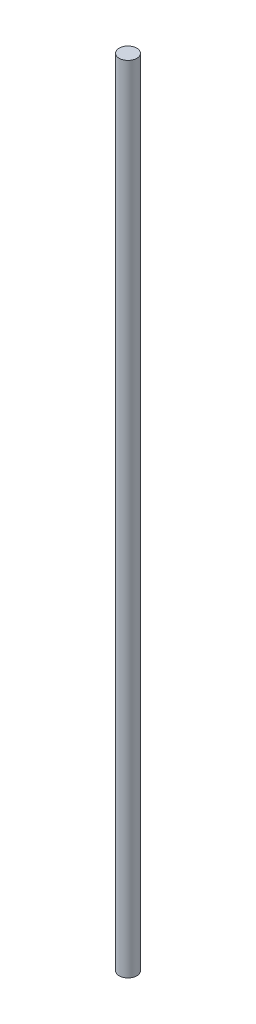
SolidWorks part; units mm, degrees
ref_plane "Спереди" through (0, 0, 0) normal (0, 0, 1) x (1, 0, 0)
ref_plane "Сверху" through (0, 0, 0) normal (0, 1, 0) x (1, 0, 0)
ref_plane "Справа" through (0, 0, 0) normal (1, 0, 0) x (0, 0, -1)
sketch "Эскиз1" plane through (0, 0, 0) normal (0, 1, 0) x (1, 0, 0)
  circle A0 centre (0, 0) radius 0.1
  dimension "D1" = 0.2
extrude "Бобышка-Вытянуть1" add sketch "Эскиз1" along normal blind 9
